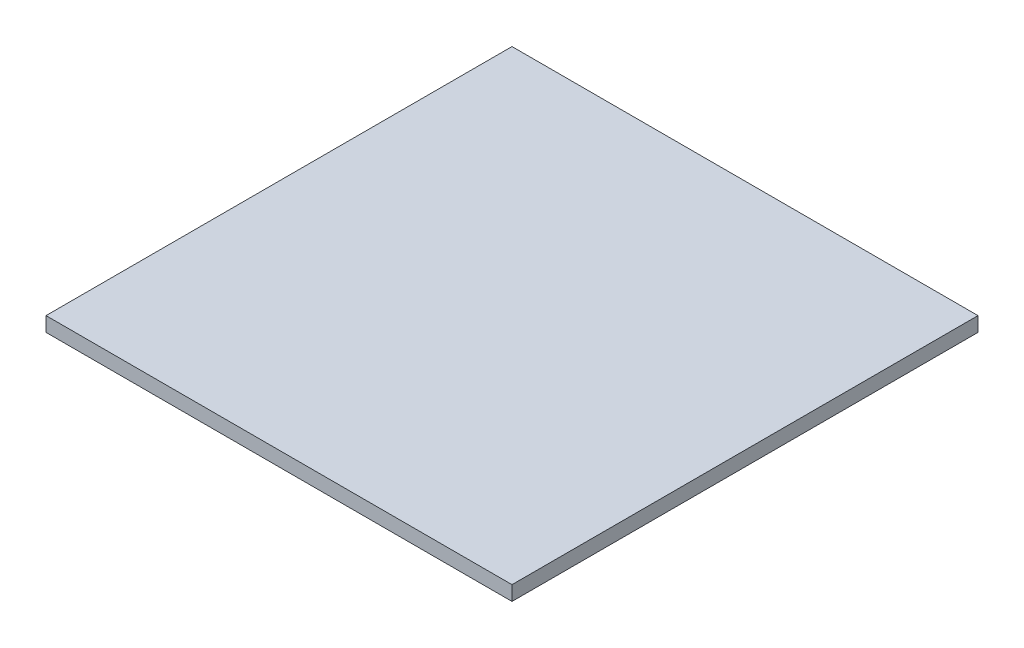
SolidWorks part; units mm, degrees
ref_plane "Front" through (0, 0, 0) normal (0, 0, 1) x (1, 0, 0)
ref_plane "Top" through (0, 0, 0) normal (0, 1, 0) x (1, 0, 0)
ref_plane "Right" through (0, 0, 0) normal (1, 0, 0) x (0, 0, -1)
sketch "Sketch1" plane through (0, 0, 0) normal (0, 1, 0) x (1, 0, 0)
  line L1 (0, 0) -> (50.8, 0)
  line L2 (0, 0) -> (0, 50.8)
  line L3 (0, 50.8) -> (50.8, 50.8)
  line L4 (50.8, 0) -> (50.8, 50.8)
  dimension "D1" = 50.8
  dimension "D2" = 50.8
extrude "Boss-Extrude1" add sketch "Sketch1" along normal blind 1.5875
